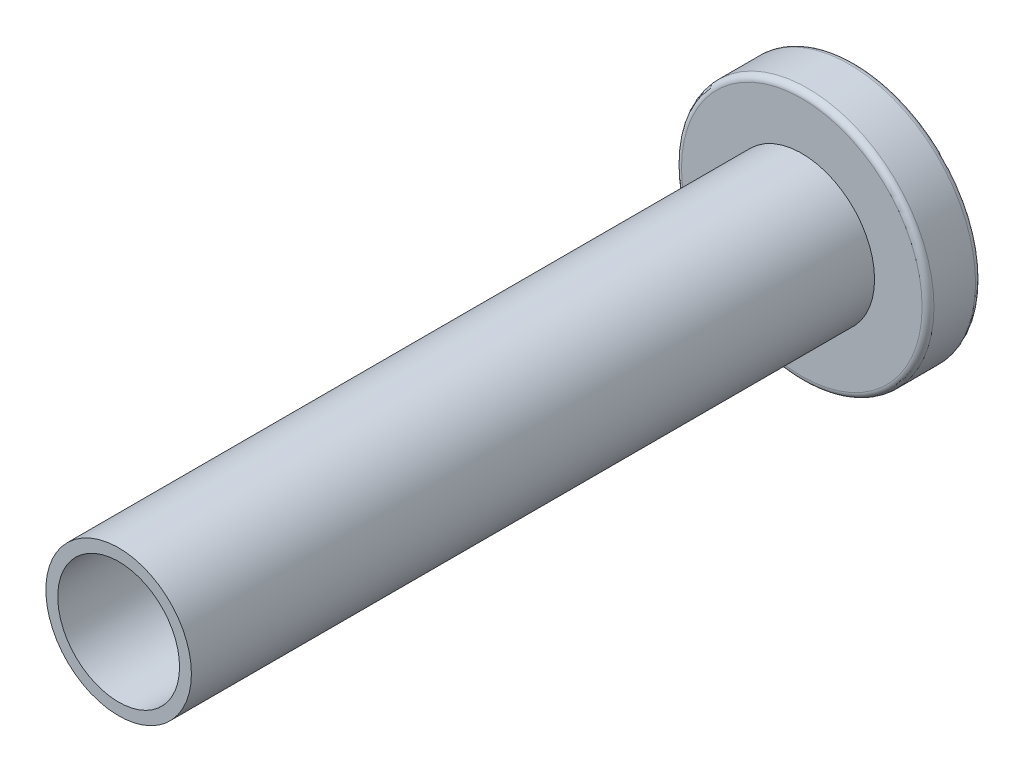
SolidWorks part; units mm, degrees
material "AISI 304"
ref_plane "前视基准面" through (0, 0, 0) normal (0, 0, 1) x (1, 0, 0)
ref_plane "上视基准面" through (0, 0, 0) normal (0, 1, 0) x (1, 0, 0)
ref_plane "右视基准面" through (0, 0, 0) normal (1, 0, 0) x (0, 0, -1)
other "Configuration Table"
sketch "草图1" plane through (0, 0, 0) normal (0, 0, 1) x (1, 0, 0)
  circle A0 centre (0, 0) radius 4.25
  dimension "D1" = 8.5
extrude "凸台-拉伸1" add sketch "草图1" along normal blind 1.8
sketch "草图2" plane through (0, 0, 1.8) normal (0, 0, 1) x (1, 0, 0)
  circle A0 centre (0, 0) radius 2.45
  circle A1 centre (0, 0) radius 2.05
  dimension "D1" = 4.9
  dimension "D2" = 4.1
extrude "凸台-拉伸2" add sketch "草图2" along normal blind 23
fillet "圆角1" radius 0.2 2 edges at (4.25, 0, 0) (4.25, 0, 1.8)
sketch "草图3" plane through (0, 0, 0) normal (0, 0, -1) x (-1, 0, 0)
  line L0 (0, 0) -> (1.4434, 0) construction
  line L1 (1.4434, 0) -> (0.7217, 1.25)
  line L2 (0.7217, 1.25) -> (-0.7217, 1.25)
  line L3 (-0.7217, 1.25) -> (-1.4434, 0)
  line L4 (-1.4434, 0) -> (-0.7217, -1.25)
  line L5 (-0.7217, -1.25) -> (0.7217, -1.25)
  line L6 (0.7217, -1.25) -> (1.4434, 0)
  circle A0 centre (0, 0) radius 1.25 construction
  dimension "D1" = 2.5
extrude "切除-拉伸1" cut sketch "草图3" against normal blind 1
sketch "草图4" plane through (0, 0, 0) normal (0, 0, -1) x (-1, 0, 0)
  point P0 (0, 0)
